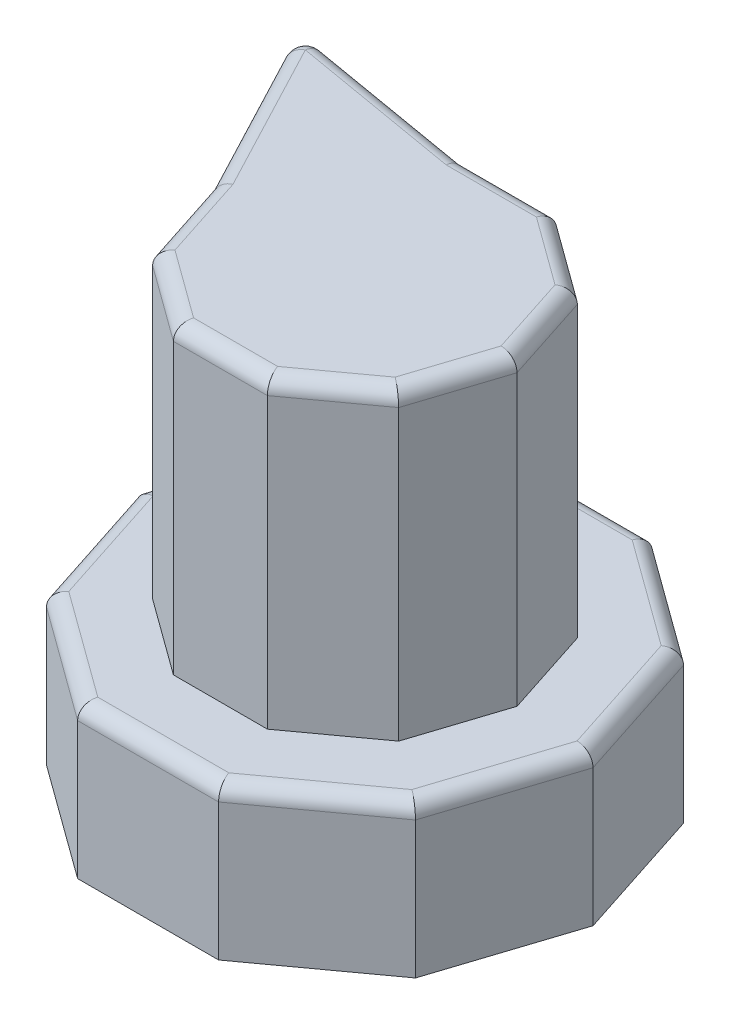
SolidWorks part; units mm, degrees
ref_plane "Front Plane" through (0, 0, 0) normal (0, 0, 1) x (1, 0, 0)
ref_plane "Top Plane" through (0, 0, 0) normal (0, 1, 0) x (1, 0, 0)
ref_plane "Right Plane" through (0, 0, 0) normal (1, 0, 0) x (0, 0, -1)
sketch "Sketch1" plane through (0, 0, 0) normal (0, 1, 0) x (1, 0, 0)
  line L1 (15, 0) -> (12.1353, 8.8168)
  line L2 (12.1353, 8.8168) -> (4.6353, 14.2658)
  line L3 (4.6353, 14.2658) -> (-4.6353, 14.2658)
  line L4 (-4.6353, 14.2658) -> (-12.1353, 8.8168)
  line L5 (-12.1353, 8.8168) -> (-15, 0)
  line L6 (-15, 0) -> (-12.1353, -8.8168)
  line L7 (-12.1353, -8.8168) -> (-4.6353, -14.2658)
  line L8 (-4.6353, -14.2658) -> (4.6353, -14.2658)
  line L9 (4.6353, -14.2658) -> (12.1353, -8.8168)
  line L10 (12.1353, -8.8168) -> (15, 0)
  circle A0 centre (0, 0) radius 14.2658 construction
  dimension "D1" = 15
extrude "Boss-Extrude1" add sketch "Sketch1" along normal blind 10
sketch "Sketch2" plane through (0, 10, 0) normal (0, 1, 0) x (1, 0, 0)
  line L1 (10, 0) -> (8.0902, 5.8779)
  line L2 (8.0902, 5.8779) -> (3.0902, 9.5106)
  line L3 (3.0902, 9.5106) -> (-3.0902, 9.5106)
  line L4 (-3.0902, 9.5106) -> (-8.0902, 5.8779)
  line L5 (-8.0902, 5.8779) -> (-10, 0)
  line L6 (-10, 0) -> (-8.0902, -5.8779)
  line L7 (-8.0902, -5.8779) -> (-3.0902, -9.5106)
  line L8 (-3.0902, -9.5106) -> (3.0902, -9.5106)
  line L9 (3.0902, -9.5106) -> (8.0902, -5.8779)
  line L10 (8.0902, -5.8779) -> (10, 0)
  circle A0 centre (0, 0) radius 9.5106 construction
  dimension "D1" = 10
extrude "Boss-Extrude2" add sketch "Sketch2" along normal blind 20
sketch "Sketch3" plane through (0, 30, 0) normal (0, 1, 0) x (1, 0, 0)
  line L0 (-10, 0) -> (-16.1803, 11.7557)
  line L1 (-16.1803, 11.7557) -> (-3.0902, 9.5106)
  line L2 (-16.1803, 11.7557) -> (0, 0)
  line L3 (-3.0902, 9.5106) -> (-10, 0)
  point P12 (-8.0902, 5.8779)
  line M5 (-3.0902, 9.5106) -> (-8.0902, 5.8779)
  line M6 (-8.0902, 5.8779) -> (-10, 0)
  dimension "D2" = 0
extrude "Boss-Extrude3" add sketch "Sketch3" against normal up to surface (30 mm away) contours L2 L0 M6 | L1 L2 M5 up to face at (0, 0, 0)
fillet "Fillet1" radius 1 21 edges at (-16.1803, 15, -11.7557) (8.3853, 10, -11.5413) (0, 10, -14.2658) (-7.1353, 10, -12.4495) (13.5676, 10, -4.4084) (13.5676, 10, 4.4084) (8.3853, 10, 11.5413) (0, 10, 14.2658) (-8.3853, 10, 11.5413) (-13.5676, 10, 4.4084) (-14.0451, 10, -2.9389) (5.5902, 30, 7.6942) (0, 30, 9.5106) (-5.5902, 30, 7.6942) (-9.0451, 30, 2.9389) (-13.0902, 30, -5.8779) (-9.6353, 30, -10.6331) (0, 30, -9.5106) (5.5902, 30, -7.6942) (9.0451, 30, -2.9389) (9.0451, 30, 2.9389)
sketch "Sketch4" plane through (0, 0, 0) normal (0, -1, 0) x (-1, 0, 0)
  line L0 (15.1613, 11.0154) -> (0, 0) construction
  line L1 (2.7911, 2.0279) -> (-1.254, -0.9111)
  line L2 (-3.0657, 1.5825) -> (0.5577, -3.4046)
  circle A0 centre (0, 0) radius 3.45
  arc A1 (15.2375, 9.9622) -> (14.1833, 11.4132) centre (14.3523, 10.4276) ccw construction
  point P12 (-1.254, -0.9111)
  dimension "D1" = 6.9
  dimension "D2" = 5
  dimension "D3" = 90
extrude "Cut-Extrude1" cut sketch "Sketch4" against normal blind 7 contours L2 A0 L1 | L1 A0 L2
